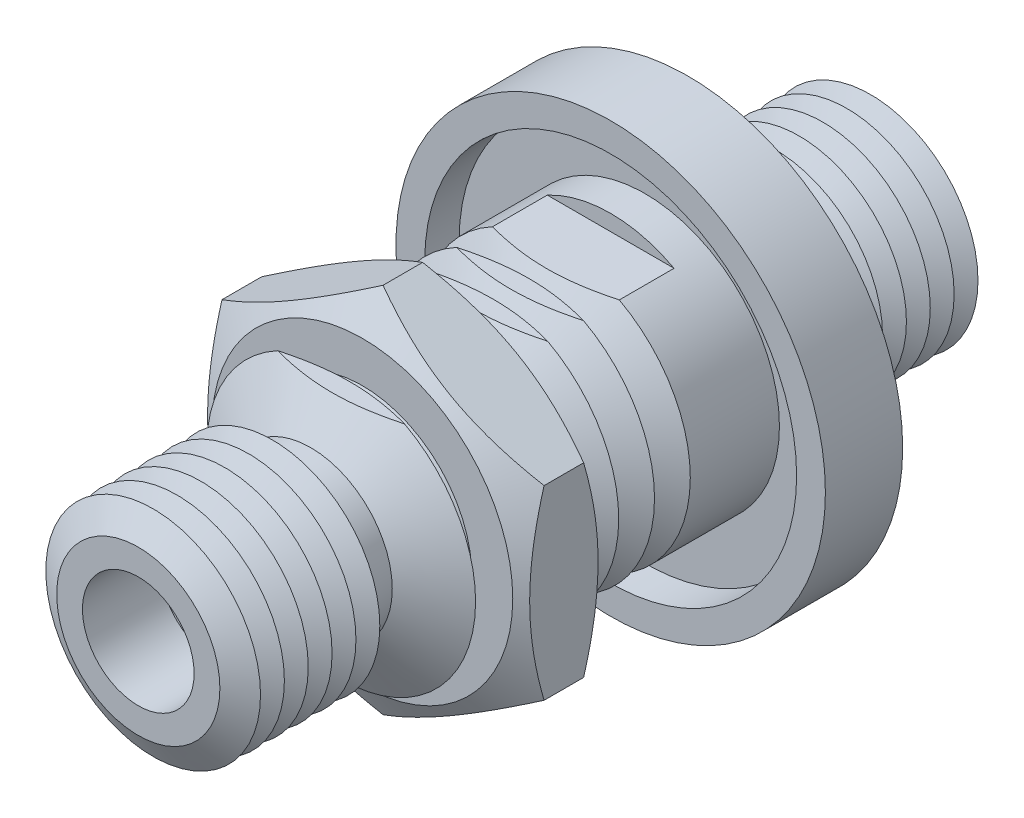
SolidWorks part; units mm, degrees
material "ASTM A36 Steel"
ref_plane "Front Plane" through (0, 0, 0) normal (0, 0, 1) x (1, 0, 0)
ref_plane "Top Plane" through (0, 0, 0) normal (0, 1, 0) x (1, 0, 0)
ref_plane "Right Plane" through (0, 0, 0) normal (1, 0, 0) x (0, 0, -1)
sketch "Sketch1" plane through (0, 0, 0) normal (1, 0, 0) x (0, 0, -1)
  line L0 (-11.684, 0) -> (5.842, 0)
  line L1 (5.842, 0) -> (5.842, 1.651)
  line L2 (5.842, 1.651) -> (8.128, 1.651)
  line L3 (8.128, 1.651) -> (8.128, 2.413)
  line L4 (8.128, 2.413) -> (7.6881, 3.175)
  line L5 (7.6881, 3.175) -> (4.1603, 3.175)
  line L6 (4.1603, 3.175) -> (3.7203, 2.413)
  line L7 (3.7203, 2.413) -> (2.286, 2.413)
  line L8 (2.286, 2.413) -> (2.286, 6.35)
  line L9 (2.286, 6.35) -> (0, 6.35)
  line L10 (0, 6.35) -> (0, 5.4991)
  line L11 (-13.6767, 3.429) -> (-13.1773, 2.564) construction
  line L12 (-13.97, 2.413) -> (-13.97, 1.651)
  line L13 (16.2423, 0) -> (25.5561, 0) construction
  line L14 (0, 5.4991) -> (1.016, 5.4991)
  line L15 (1.016, 5.4991) -> (1.016, 3.9751)
  line L16 (1.016, 3.9751) -> (-7.9703, 3.9751)
  line L17 (-13.1773, 2.564) -> (-12.6779, 3.429) construction
  line L18 (-7.9703, 3.9751) -> (-8.8722, 2.413)
  line L19 (-8.8722, 2.413) -> (-9.5623, 2.413)
  line L20 (-9.5623, 2.413) -> (-10.0023, 3.175)
  line L21 (-10.0023, 3.175) -> (-13.5301, 3.175)
  line L22 (-13.5301, 3.175) -> (-13.97, 2.413)
  line L23 (-12.6779, 3.429) -> (-13.6767, 3.429) construction
  line L24 (-8.1169, 4.2291) -> (-7.4411, 3.0586) construction
  line L25 (-7.4411, 3.0586) -> (-6.7653, 4.2291) construction
  line L26 (-6.7653, 4.2291) -> (-8.1169, 4.2291) construction
  line L27 (-13.97, 1.651) -> (-11.684, 1.651)
  line L28 (-11.684, 1.651) -> (-11.684, 0)
  line L29 (7.8347, 3.429) -> (7.3353, 2.564) construction
  line L30 (7.3353, 2.564) -> (6.8359, 3.429) construction
  line L31 (6.8359, 3.429) -> (7.8347, 3.429) construction
  point P21 (-12.8245, 3.175)
  point P29 (-6.9119, 3.9751)
  point P35 (6.9825, 3.175)
  dimension "D3" = 2.286
  dimension "D4" = 0.762
  dimension "D5" = 60
  dimension "D6" = 60
  dimension "D7" = 1.524
  dimension "D8" = 6.35
  dimension "D9" = 12.7
  dimension "D10" = 0.7056
  dimension "D11" = 13.97
  dimension "D12" = 7.9502
  dimension "D13" = 6.35
  dimension "D14" = 4.826
  dimension "D15" = 0.254
  dimension "D16" = 3.5278
  dimension "D17" = 1.0583
  dimension "D18" = 0.254
  dimension "D19" = 2.032
  dimension "D20" = 1.016
  dimension "D21" = 1.524
  dimension "D22" = 2.286
  dimension "D23" = 0.7056
  dimension "D24" = 0.254
  dimension "D25" = 3.5278
  dimension "D26" = 22.098
revolve "Revolve1" add sketch "Sketch1" angle 360 about L13
ref_axis "Axis1" through (0, 0, 15.0749) along (0, 0, -1)
sketch "Sketch2" plane through (0, 0, 0) normal (1, 0, 0) x (0, 0, -1)
  line L0 (7.8347, 3.429) -> (7.3353, 2.564) construction
  line L1 (6.8359, 3.429) -> (7.8347, 3.429) construction
  line L2 (7.3353, 2.564) -> (6.8359, 3.429) construction
  line L3 (7.8347, 3.429) -> (7.3353, 2.564)
  line L4 (6.8359, 3.429) -> (7.8347, 3.429)
  line L5 (7.3353, 2.564) -> (6.8359, 3.429)
revolve "Cut-Revolve1" cut sketch "Sketch2" angle 360 about axis through (0, 0, 15.0749) along (0, 0, -1)
pattern_linear "LPattern1" count 5 spacing 0.7056 along (0, 0, 1) of "Cut-Revolve1"
sketch "Sketch3" plane through (0, 0, 0) normal (1, 0, 0) x (0, 0, -1)
  line L0 (-13.1773, 2.564) -> (-12.6779, 3.429) construction
  line L1 (-12.6779, 3.429) -> (-13.6767, 3.429) construction
  line L2 (-13.6767, 3.429) -> (-13.1773, 2.564) construction
  line L3 (-13.1773, 2.564) -> (-12.6779, 3.429)
  line L4 (-12.6779, 3.429) -> (-13.6767, 3.429)
  line L5 (-13.6767, 3.429) -> (-13.1773, 2.564)
revolve "Cut-Revolve2" cut sketch "Sketch3" angle 360 about axis through (0, 0, 15.0749) along (0, 0, -1)
pattern_linear "LPattern2" count 5 spacing 0.7056 along (0, 0, -1) of "Cut-Revolve2"
sketch "Sketch4" plane through (0, 0, 0) normal (1, 0, 0) x (0, 0, -1)
  line L0 (-7.4411, 3.0586) -> (-6.7653, 4.2291) construction
  line L1 (-6.7653, 4.2291) -> (-8.1169, 4.2291) construction
  line L2 (-8.1169, 4.2291) -> (-7.4411, 3.0586) construction
  line L3 (-7.4411, 3.0586) -> (-6.7653, 4.2291)
  line L4 (-6.7653, 4.2291) -> (-8.1169, 4.2291)
  line L5 (-8.1169, 4.2291) -> (-7.4411, 3.0586)
revolve "Cut-Revolve3" cut sketch "Sketch4" angle 360 about axis through (0, 0, 15.0749) along (0, 0, -1)
pattern_linear "LPattern3" count 6 spacing 1.0583 along (0, 0, -1) of "Cut-Revolve3"
sketch "Sketch5" plane through (0, 0, 0) normal (0, 0, 1) x (1, 0, 0)
  line L1 (-7.1476, 8.2168) -> (7.1476, 8.2168)
  line L2 (-7.1476, 8.2168) -> (-7.1476, 3.5052)
  line L3 (-7.1476, 3.5052) -> (7.1476, 3.5052)
  line L4 (7.1476, 8.2168) -> (7.1476, 3.5052)
  point P4 (0, 8.2168)
  dimension "D1" = 3.5052
extrude "Cut-Extrude1" cut sketch "Sketch5" along normal through all
sketch "Sketch6" plane through (0, 0, 0) normal (1, 0, 0) x (0, 0, -1)
  line L0 (-4.953, 1.2942) -> (-4.953, 4.445)
  line L1 (-4.953, 4.445) -> (-6.1468, 6.5127)
  line L3 (-6.1468, 6.5127) -> (-7.3406, 4.445)
  line L4 (-7.3406, 4.445) -> (-7.3406, 1.2942)
  line L5 (-7.3406, 1.2942) -> (-4.953, 1.2942)
  line L7 (8.128, 2.413) -> (7.6881, 3.175) construction
  line L8 (4.1603, 3.175) -> (3.7203, 2.413) construction
  line L9 (0, 6.35) -> (0, 5.4991) construction
  line L10 (-19.8442, 0) -> (-15.939, 0) construction
  dimension "D2" = 4.953
  dimension "D3" = 2.3876
  dimension "D4" = 8.89
revolve "Revolve2" add sketch "Sketch6" angle 360 about L10
sketch "Sketch7" plane through (0, 0, 7.3406) normal (0, 0, 1) x (1, 0, 0)
  line L1 (0, 5.4993) -> (-4.7625, 2.7496)
  line L2 (-4.7625, 2.7496) -> (-4.7625, -2.7496)
  line L3 (-4.7625, -2.7496) -> (0, -5.4993)
  line L4 (0, -5.4993) -> (4.7625, -2.7496)
  line L5 (4.7625, -2.7496) -> (4.7625, 2.7496)
  line L6 (4.7625, 2.7496) -> (0, 5.4993)
  circle A0 centre (0, 0) radius 4.7625 construction
  dimension "D1" = 9.525
extrude "Cut-Extrude2" cut sketch "Sketch7" against normal blind 2.54 flip side to cut
